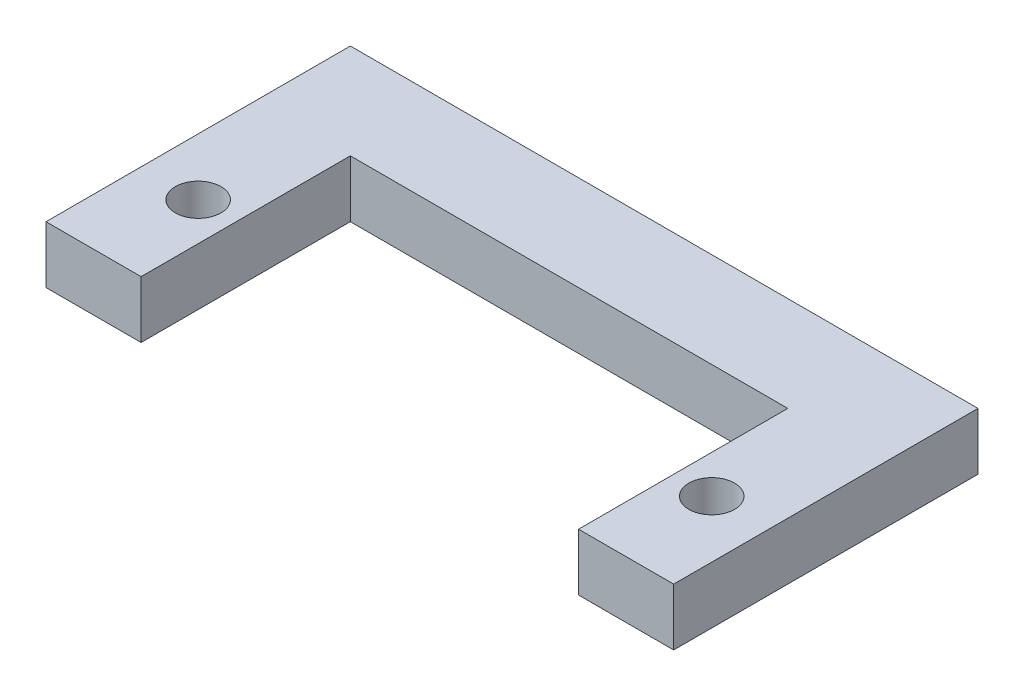
SolidWorks part; units mm, degrees
ref_plane "Front Plane" through (0, 0, 0) normal (0, 0, 1) x (1, 0, 0)
ref_plane "Top Plane" through (0, 0, 0) normal (0, 1, 0) x (1, 0, 0)
ref_plane "Right Plane" through (0, 0, 0) normal (1, 0, 0) x (0, 0, -1)
sketch "Sketch4" plane through (0, 0, 0) normal (0, 1, 0) x (1, 0, 0)
  line L1 (5, -5) -> (28, -5)
  line L3 (0, 0) -> (33, 0)
  line L6 (0, 0) -> (0, -16)
  line L7 (0, -16) -> (5, -16)
  line L8 (5, -5) -> (5, -16)
  line L10 (33, 0) -> (33, -16)
  line L11 (33, -16) -> (28, -16)
  line L12 (28, -5) -> (28, -16)
  circle A0 centre (3, -11) radius 1.2
  circle A1 centre (30, -11) radius 1.2
  point P3 (0, 0)
  point P15 (0, 0)
  point P16 (31, -4.6865)
  point P17 (31, -2.5046)
  point P19 (29.0458, -21.2367)
  dimension "D4" = 2.4
  dimension "D5" = 2.4
  dimension "D8" = 6
  dimension "D9" = 2
  dimension "D10" = 2
  dimension "D1" = 23
  dimension "D2" = 5
  dimension "D3" = 5
  dimension "D6" = 5
  dimension "D7" = 11
extrude "Boss-Extrude3" add sketch "Sketch4" along normal blind 3
